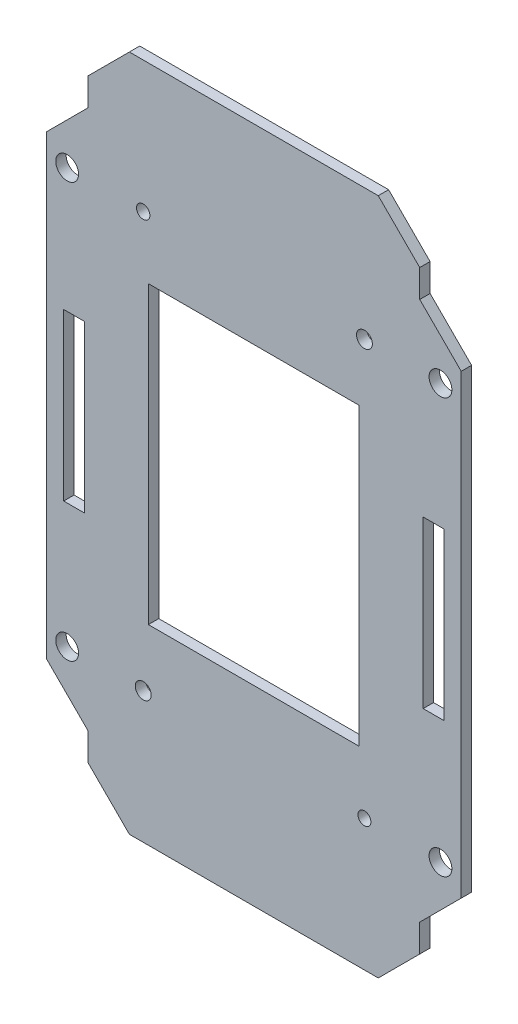
SolidWorks part; units mm, degrees
material "碳纤维板_1600kg_m3"
ref_plane "前视基准面" through (0, 0, 0) normal (0, 0, 1) x (1, 0, 0)
ref_plane "上视基准面" through (0, 0, 0) normal (0, 1, 0) x (1, 0, 0)
ref_plane "右视基准面" through (0, 0, 0) normal (1, 0, 0) x (0, 0, -1)
other "Configuration Table"
sketch "草图1" plane through (0, 0, 0) normal (0, 0, 1) x (1, 0, 0)
  line L0 (14.7991, -21.3549) -> (15.6991, -21.3549) construction
  line L1 (-15.2491, 21.3549) -> (15.2491, 21.3549)
  line L2 (-15.2491, 21.3549) -> (-15.2491, -21.3549)
  line L3 (-15.2491, -21.3549) -> (15.2491, -21.3549)
  line L4 (15.2491, 21.3549) -> (15.2491, -21.3549)
  line L5 (-15.2491, 21.3549) -> (15.2491, -21.3549) construction
  line L6 (-15.2491, -21.3549) -> (15.2491, 21.3549) construction
  line L32 (24, -39) -> (24, -43)
  line L33 (24, -43) -> (18, -49)
  line L34 (18, -49) -> (-18, -49)
  line L35 (-18, -49) -> (-24, -43)
  line L36 (-24, -43) -> (-24, -39)
  line L37 (-24, -39) -> (-30, -33)
  line L38 (-30, -33) -> (-30, 33)
  line L39 (-30, 33) -> (-24, 39)
  line L40 (-24, 39) -> (-24, 43)
  line L41 (-24, 43) -> (-18, 49)
  line L42 (-18, 49) -> (18, 49)
  line L43 (18, 49) -> (24, 43)
  line L44 (24, 43) -> (24, 39)
  line L45 (24, 39) -> (30, 33)
  line L46 (30, 33) -> (30, -33)
  line L47 (30, -33) -> (24, -39)
  line L48 (-27.5, -12) -> (-24.5, -12)
  line L49 (-24.5, -12) -> (-24.5, 12)
  line L50 (-24.5, 12) -> (-27.5, 12)
  line L51 (-27.5, 12) -> (-27.5, -12)
  line L52 (24.5, -12) -> (27.5, -12)
  line L53 (27.5, -12) -> (27.5, 12)
  line L54 (27.5, 12) -> (24.5, 12)
  line L55 (24.5, 12) -> (24.5, -12)
  circle A0 centre (16, 30) radius 1.15
  circle A1 centre (-16, -30) radius 1.15
  circle A2 centre (16, -30) radius 0.94
  circle A3 centre (-16, 30) radius 0.9677
  circle A12 centre (-27, -30) radius 1.65
  circle A13 centre (-27, 30) radius 1.65
  circle A14 centre (27, -30) radius 1.65
  circle A15 centre (27, 30) radius 1.65
  point P8 (0, 0)
extrude "Pixhawk正装减振托板_绑带槽_四M3孔" add sketch "草图1" along normal blind 1.5
